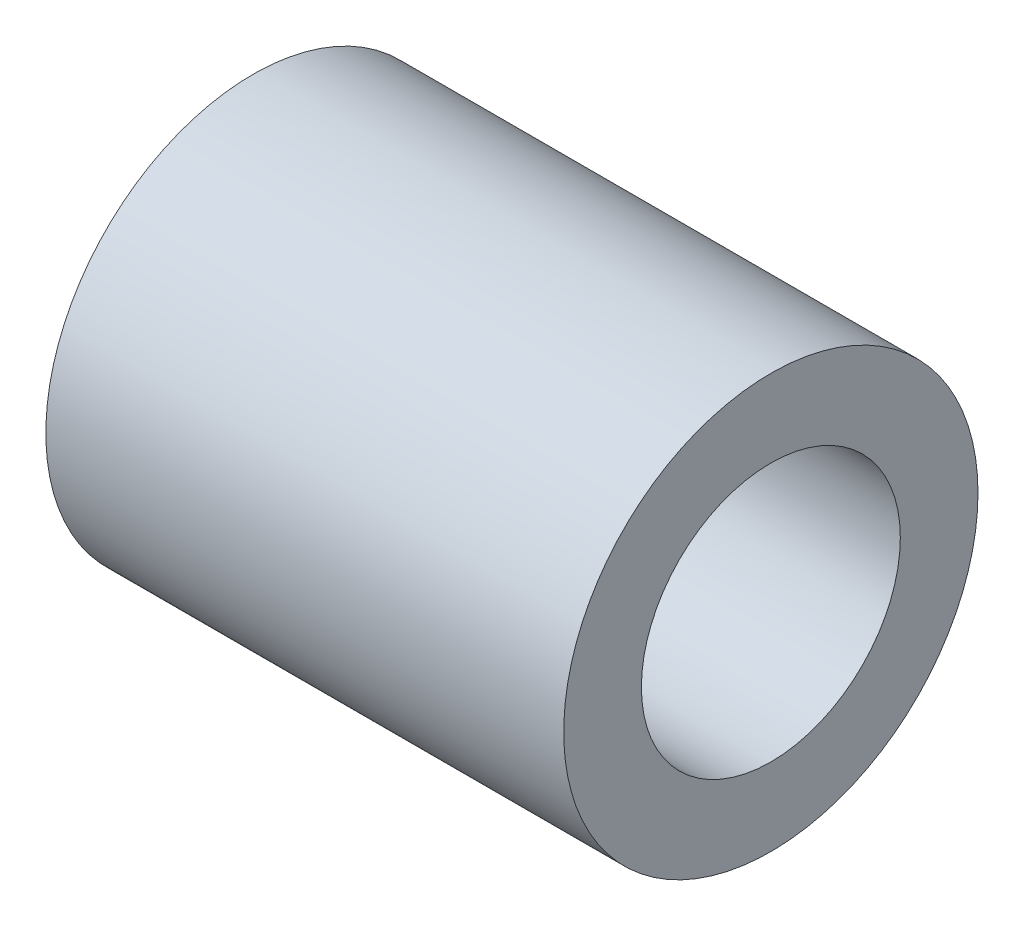
SolidWorks part; units mm, degrees
ref_plane "Front Plane" through (0, 0, 0) normal (0, 0, 1) x (1, 0, 0)
ref_plane "Top Plane" through (0, 0, 0) normal (0, 1, 0) x (1, 0, 0)
ref_plane "Right Plane" through (0, 0, 0) normal (1, 0, 0) x (0, 0, -1)
sketch "Sketch1" plane through (0, 0, 0) normal (1, 0, 0) x (0, 0, -1)
  circle A0 centre (0, 0) radius 8
  circle A1 centre (0, 0) radius 5
  dimension "D1" = 16
  dimension "D2" = 10
extrude "Boss-Extrude1" add sketch "Sketch1" along normal blind 20
